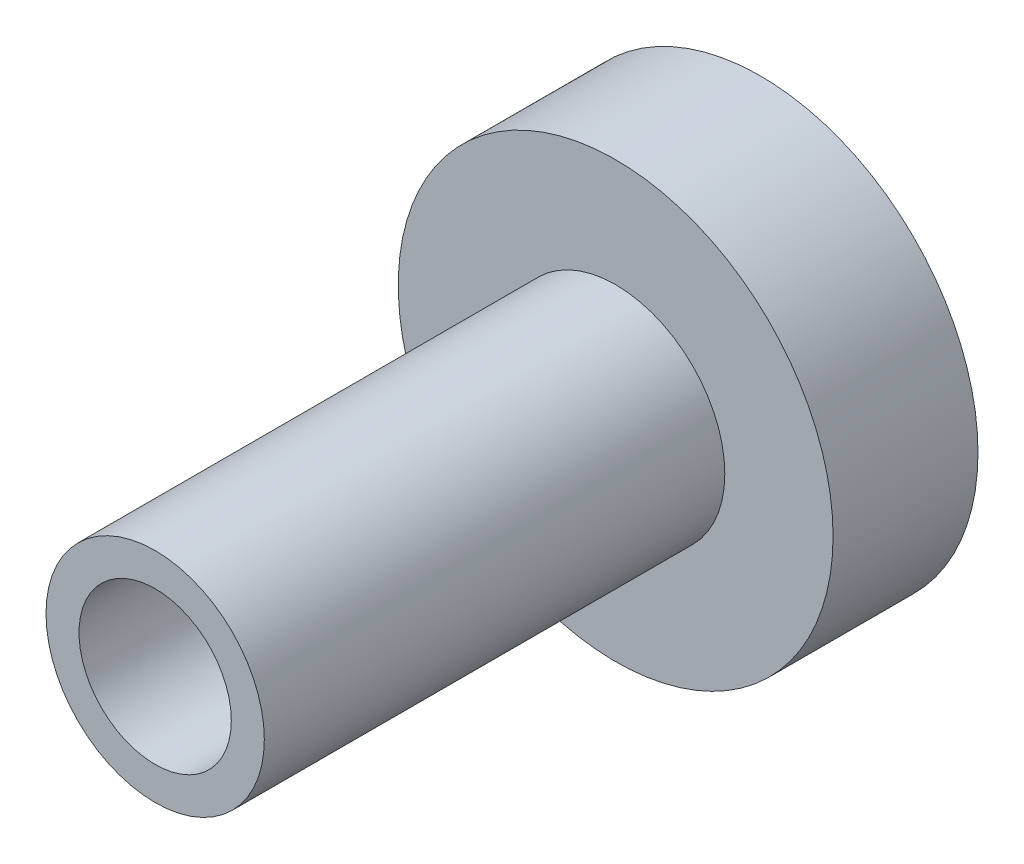
SolidWorks part; units mm, degrees
ref_plane "Front Plane" through (0, 0, 0) normal (0, 0, 1) x (1, 0, 0)
ref_plane "Top Plane" through (0, 0, 0) normal (0, 1, 0) x (1, 0, 0)
ref_plane "Right Plane" through (0, 0, 0) normal (1, 0, 0) x (0, 0, -1)
sketch "Sketch1" plane through (0, 0, 0) normal (0, 0, 1) x (1, 0, 0)
  circle A0 centre (0, 0) radius 11.85
  circle A1 centre (0, 0) radius 4.15
  dimension "D1" = 23.7
  dimension "D2" = 8.3
extrude "Boss-Extrude1" add sketch "Sketch1" along normal blind 33
sketch "Sketch2" plane through (0, 0, 33) normal (0, 0, 1) x (1, 0, 0)
  circle A0 centre (0, 0) radius 5.95
  circle A1 centre (0, 0) radius 11.85
  circle A2 centre (0, 0) radius 11.85 construction
  dimension "D1" = 11.9
extrude "Cut-Extrude1" cut sketch "Sketch2" against normal blind 25.1
